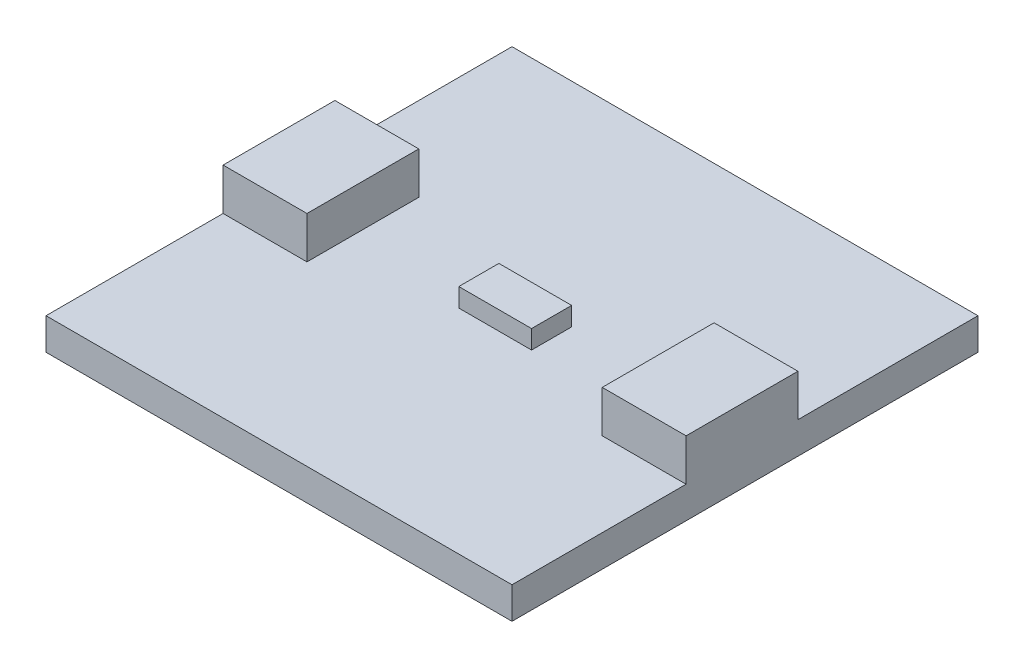
SolidWorks part; units mm, degrees
ref_plane "Front Plane" through (0, 0, 0) normal (0, 0, 1) x (1, 0, 0)
ref_plane "Top Plane" through (0, 0, 0) normal (0, 1, 0) x (1, 0, 0)
ref_plane "Right Plane" through (0, 0, 0) normal (1, 0, 0) x (0, 0, -1)
sketch "Sketch1" plane through (0, 0, 0) normal (0, 1, 0) x (1, 0, 0)
  line L1 (0, 0) -> (25.4, 0)
  line L2 (0, 0) -> (0, -25.4)
  line L3 (0, -25.4) -> (25.4, -25.4)
  line L4 (25.4, 0) -> (25.4, -25.4)
  dimension "D1" = 25.4
  dimension "D2" = 25.4
extrude "Boss-Extrude1" add sketch "Sketch1" along normal blind 1.7272
sketch "Sketch2" plane through (0, 1.7272, 0) normal (0, 1, 0) x (1, 0, 0)
  line L0 (0, 0) -> (0, -25.4) construction
  line L1 (0, -9.652) -> (4.572, -9.652)
  line L2 (0, -9.652) -> (0, -15.748)
  line L3 (0, -15.748) -> (4.572, -15.748)
  line L4 (4.572, -9.652) -> (4.572, -15.748)
  line L5 (25.4, -25.4) -> (25.4, 0) construction
  line L6 (20.828, -9.8145) -> (25.4, -9.8145)
  line L7 (20.828, -9.8145) -> (20.828, -15.9105)
  line L8 (20.828, -15.9105) -> (25.4, -15.9105)
  line L9 (25.4, -9.8145) -> (25.4, -15.9105)
  point P6 (0, -12.7)
  point P7 (0, -12.7)
  dimension "D1" = 4.572
  dimension "D2" = 6.096
extrude "Boss-Extrude2" add sketch "Sketch2" along normal blind 2.286
sketch "Sketch3" plane through (0, 1.7272, 0) normal (0, 1, 0) x (1, 0, 0)
  line L0 (25.4, 0) -> (0, 0) construction
  line L1 (10.8889, -11.6038) -> (14.8546, -11.6038)
  line L2 (10.8889, -11.6038) -> (10.8889, -13.7886)
  line L3 (10.8889, -13.7886) -> (14.8546, -13.7886)
  line L4 (14.8546, -11.6038) -> (14.8546, -13.7886)
  line L5 (25.4, -25.4) -> (25.4, -15.9105) construction
  point P6 (14.8546, -12.6962)
  dimension "D1" = 11.6038
  dimension "D2" = 10.5454
  dimension "D3" = 2.1848
  dimension "D4" = 3.9657
extrude "Boss-Extrude3" add sketch "Sketch3" along normal blind 1.016
